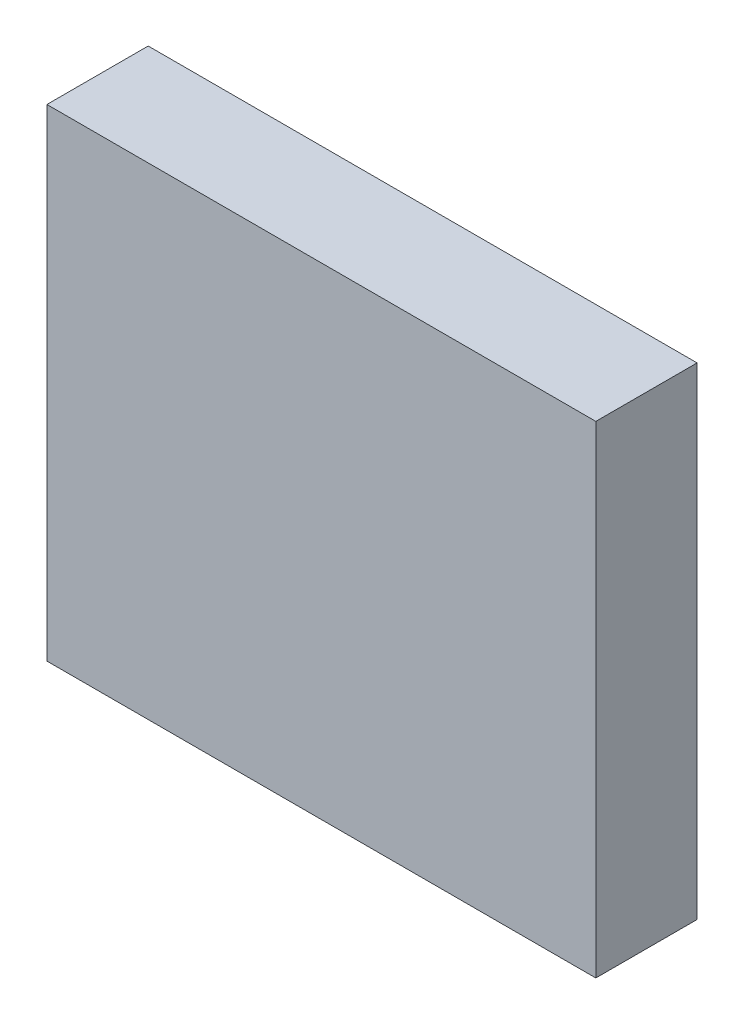
SolidWorks part; units mm, degrees
material "Alliage 1060"
ref_plane "Plan de face" through (0, 0, 0) normal (0, 0, 1) x (1, 0, 0)
ref_plane "Plan de dessus" through (0, 0, 0) normal (0, 1, 0) x (1, 0, 0)
ref_plane "Plan de droite" through (0, 0, 0) normal (1, 0, 0) x (0, 0, -1)
sketch "Esquisse1" plane through (0, 0, 0) normal (0, 0, 1) x (1, 0, 0)
  line L1 (-34.417, 30.226) -> (34.417, 30.226)
  line L2 (-34.417, 30.226) -> (-34.417, -30.226)
  line L3 (-34.417, -30.226) -> (34.417, -30.226)
  line L4 (34.417, 30.226) -> (34.417, -30.226)
  line L5 (-34.417, 30.226) -> (34.417, -30.226) construction
  line L6 (-34.417, -30.226) -> (34.417, 30.226) construction
  point P0 (0, 0)
  dimension "D1" = 68.834
  dimension "D2" = 60.452
extrude "Boss.-Extru.1" add sketch "Esquisse1" along normal blind 12.7
sketch "Esquisse2" plane through (0, 0, 12.7) normal (0, 0, 1) x (1, 0, 0)
  line L1 (34.417, -30.226) -> (34.417, 30.226) construction
  line L4 (34.417, 30.226) -> (-34.417, 30.226) construction
  line L5 (34.417, 0) -> (-34.417, 0) construction
  line L6 (-34.417, 30.226) -> (-34.417, -30.226) construction
  line L7 (0, 30.226) -> (0, -30.226) construction
  line L8 (-34.417, -30.226) -> (34.417, -30.226) construction
  circle A0 centre (24.892, 20.701) radius 3.175
  circle A1 centre (-24.892, 20.701) radius 3.175
  circle A2 centre (-24.892, -20.701) radius 3.175
  circle A3 centre (24.892, -20.701) radius 3.175
  dimension "D1" = 6.35
  dimension "D2" = 6.35
  dimension "D3" = 6.35
extrude "Enlèv. mat.-Extru.1" [suppressed] cut sketch "Esquisse2" against normal blind 12.7
